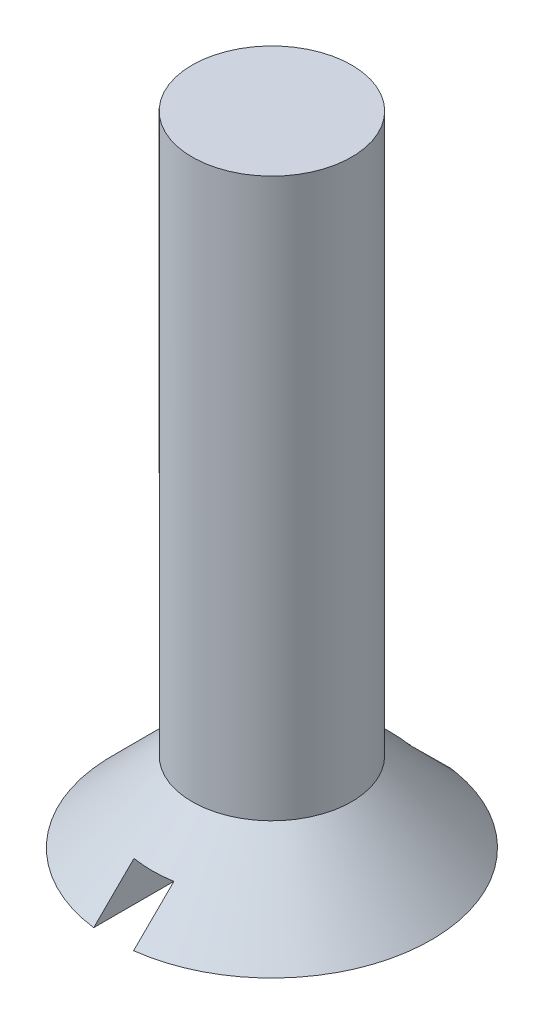
SolidWorks part; units mm, degrees
ref_plane "Front" through (0, 0, 0) normal (0, 0, 1) x (1, 0, 0)
ref_plane "Top" through (0, 0, 0) normal (0, 1, 0) x (1, 0, 0)
ref_plane "Right" through (0, 0, 0) normal (1, 0, 0) x (0, 0, -1)
sketch "Sketch1" plane through (0, 0, 0) normal (0, 0, 1) x (1, 0, 0)
  line L0 (0, 8) -> (0, 0)
  line L1 (0, 0) -> (-2, 0)
  line L2 (-2, 0) -> (-1, 1)
  line L3 (-1, 1) -> (-1, 8)
  line L4 (-1, 8) -> (0, 8)
  dimension "D1" = 8
  dimension "D2" = 1
  dimension "D3" = 45
  dimension "D4" = 2
revolve "Revolve1" add sketch "Sketch1" angle 360 about L0
sketch "Sketch2" plane through (0, 0, 0) normal (0, -1, 0) x (1, 0, 0)
  line L0 (0.25, 2) -> (0.25, -2)
  line L1 (0.25, -2) -> (-0.25, -2)
  line L2 (-0.25, -2) -> (-0.25, 2)
  line L3 (-0.25, 2) -> (0.25, 2)
  circle A1 centre (0, 0) radius 2 construction
  dimension "D1" = 0.25
  dimension "D2" = 0.25
extrude "Cut-Extrude1" cut sketch "Sketch2" against normal blind 0.5
